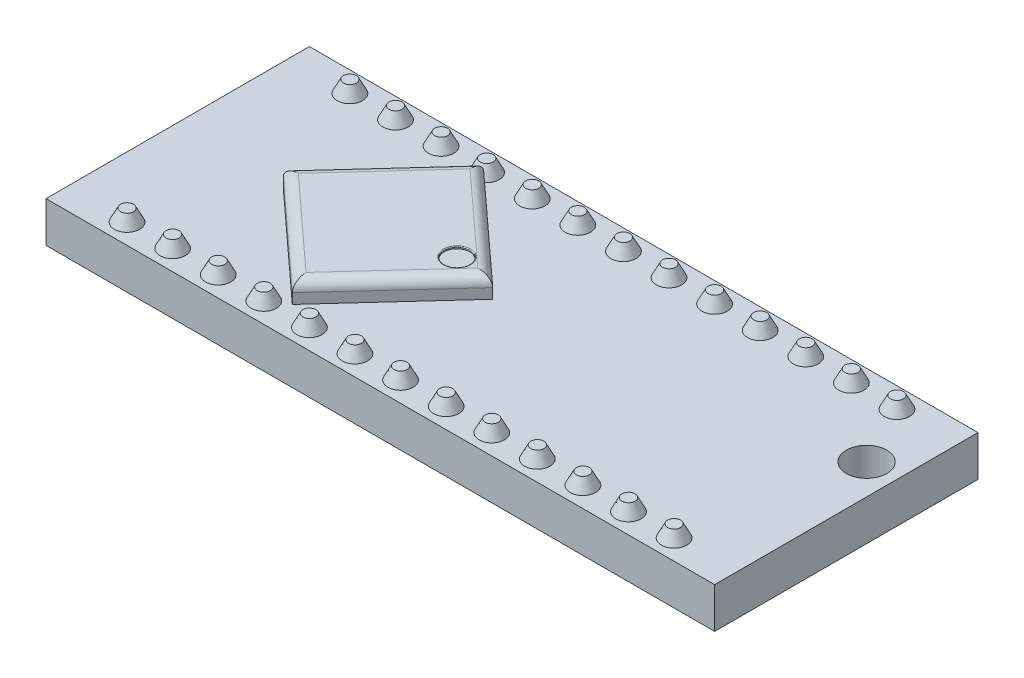
SolidWorks part; units mm, degrees
ref_plane "Front Plane" through (0, 0, 0) normal (0, 0, 1) x (1, 0, 0)
ref_plane "Top Plane" through (0, 0, 0) normal (0, 1, 0) x (1, 0, 0)
ref_plane "Right Plane" through (0, 0, 0) normal (1, 0, 0) x (0, 0, -1)
sketch "Sketch1" plane through (0, 0, 0) normal (0, 1, 0) x (1, 0, 0)
  line L1 (-16.5, 6.5) -> (16.5, 6.5)
  line L2 (-16.5, 6.5) -> (-16.5, -6.5)
  line L3 (-16.5, -6.5) -> (16.5, -6.5)
  line L4 (16.5, 6.5) -> (16.5, -6.5)
  line L5 (-16.5, 6.5) -> (16.5, -6.5) construction
  line L6 (-16.5, -6.5) -> (16.5, 6.5) construction
  point P0 (0, 0)
  dimension "D1" = 13
  dimension "D2" = 33
extrude "Boss-Extrude1" add sketch "Sketch1" along normal blind 2
sketch "Sketch2" plane through (0, 2, 0) normal (0, 1, 0) x (1, 0, 0)
  line L0 (-11.0637, -0.2218) -> (-5.8971, -4.9448)
  line L1 (-11.0637, -0.2218) -> (-6.3407, 4.9448)
  line L2 (-5.8971, -4.9448) -> (-1.1741, 0.2218)
  line L3 (-6.3407, 4.9448) -> (-1.1741, 0.2218)
  line L4 (-11.0637, -0.2218) -> (-1.1741, 0.2218) construction
  line L5 (-5.8971, -4.9448) -> (-6.3407, 4.9448) construction
  point P0 (0, 0)
  point P1 (-6.1189, 0)
  dimension "D1" = 7
  dimension "D2" = 7
extrude "Boss-Extrude2" add sketch "Sketch2" along normal blind 1
fillet "Fillet1" radius 0.5 4 edges at (-3.7574, 3, -2.5833) (-3.5356, 3, 2.3615) (-8.4804, 3, 2.5833) (-8.7022, 3, -2.3615)
sketch "Sketch3" plane through (0, 3, 0) normal (0, 1, 0) x (1, 0, 0)
  circle A0 centre (-2.8689, 0.1515) radius 0.6312
extrude "Cut-Extrude1" cut sketch "Sketch3" against normal blind 0.1
fillet "Fillet2" radius 0.04 1 edges at (-2.8689, 3, 0.4797)
sketch "Sketch4" plane through (0, 2, 0) normal (0, 1, 0) x (1, 0, 0)
  line L0 (16.5, 6.5) -> (-16.5, 6.5) construction
  line L1 (-16.5, 6.5) -> (-16.5, -6.5) construction
  line L3 (-55, 0) -> (55, 0) construction
  circle A0 centre (-13.5, 5.5) radius 0.625
  circle A1 centre (-11.25, 5.5) radius 0.625
  circle A2 centre (-9, 5.5) radius 0.625
  circle A3 centre (-6.75, 5.5) radius 0.625
  circle A4 centre (-4.5, 5.5) radius 0.625
  circle A5 centre (-2.25, 5.5) radius 0.625
  circle A6 centre (0, 5.5) radius 0.625
  circle A7 centre (2.25, 5.5) radius 0.625
  circle A8 centre (4.5, 5.5) radius 0.625
  circle A9 centre (6.75, 5.5) radius 0.625
  circle A10 centre (9, 5.5) radius 0.625
  circle A11 centre (11.25, 5.5) radius 0.625
  circle A12 centre (13.5, 5.5) radius 0.625
  circle A13 centre (-13.5, -5.5) radius 0.625
  circle A14 centre (-11.25, -5.5) radius 0.625
  circle A15 centre (-9, -5.5) radius 0.625
  circle A16 centre (-6.75, -5.5) radius 0.625
  circle A17 centre (-4.5, -5.5) radius 0.625
  circle A18 centre (-2.25, -5.5) radius 0.625
  circle A19 centre (0, -5.5) radius 0.625
  circle A20 centre (2.25, -5.5) radius 0.625
  circle A21 centre (4.5, -5.5) radius 0.625
  circle A22 centre (6.75, -5.5) radius 0.625
  circle A23 centre (9, -5.5) radius 0.625
  circle A24 centre (11.25, -5.5) radius 0.625
  circle A25 centre (13.5, -5.5) radius 0.625
  dimension "D1" = 1
  dimension "D3" = 1.25
  dimension "D2" = 3
  dimension "D4" = 13
  dimension "D5" = 13
extrude "Boss-Extrude3" add sketch "Sketch4" along normal blind 0.6 draft 27 contours A0 | A1 | A2 | A3 | A4 | A5 | A6 | A7 | A8 | A9 | A10 | A11 | A12 | A25 | A24 | A23 | A22 | A21 | A20 | A19 | A18 | A17 | A16 | A15 | A13 | A14
sketch "Sketch6" plane through (0, 3, 0) normal (0, 1, 0) x (1, 0, 0)
  spline S0 degree 1 poles (-7.437, -2.4519) (-7.5994, 1.7699) knots 0 0 1 1
  text T0 "Atmega32" font "Century Gothic" height 0.6
  dimension "D1" = 1.8805
  dimension "D2" = 5.5564
  dimension "D3" = 5.7188
  dimension "D4" = 2.4684
  dimension "D5" = 4.2384
  dimension "D6" = 6.6903
sketch "Sketch7" plane through (0, 2, 0) normal (0, 1, 0) x (1, 0, 0)
  line L0 (16.5, -6.5) -> (16.5, 6.5) construction
  line L2 (16.5, 6.5) -> (-16.5, 6.5) construction
  circle A0 centre (15, 2.5) radius 1
  point P6 (15.0918, 6.5)
  dimension "D1" = 2
  dimension "D2" = 1.5
  dimension "D3" = 4
extrude "Cut-Extrude2" cut sketch "Sketch7" against normal blind 3
